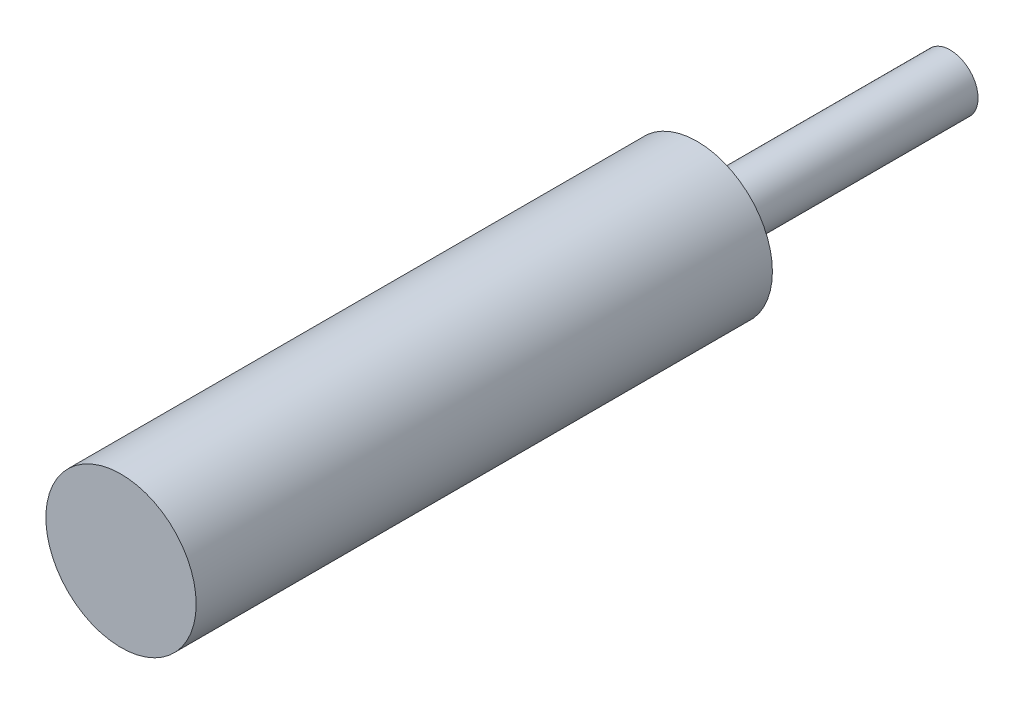
SolidWorks part; units mm, degrees
ref_plane "Front Plane" through (0, 0, 0) normal (0, 0, 1) x (1, 0, 0)
ref_plane "Top Plane" through (0, 0, 0) normal (0, 1, 0) x (1, 0, 0)
ref_plane "Right Plane" through (0, 0, 0) normal (1, 0, 0) x (0, 0, -1)
sketch "Sketch2" plane through (0, 0, 0) normal (0, 0, 1) x (1, 0, 0)
  circle A0 centre (0, 0) radius 2.325
  dimension "D1" = 4.65
extrude "Boss-Extrude1" add sketch "Sketch2" against normal blind 25.65
sketch "Sketch3" plane through (0, 0, -25.65) normal (0, 0, -1) x (-1, 0, 0)
  circle A0 centre (0, 0) radius 0.8618
  circle A1 centre (0, 0) radius 2.325
  dimension "D1" = 1.7237
  dimension "D2" = 4.65
extrude "Cut-Extrude1" cut sketch "Sketch3" against normal blind 7.825
